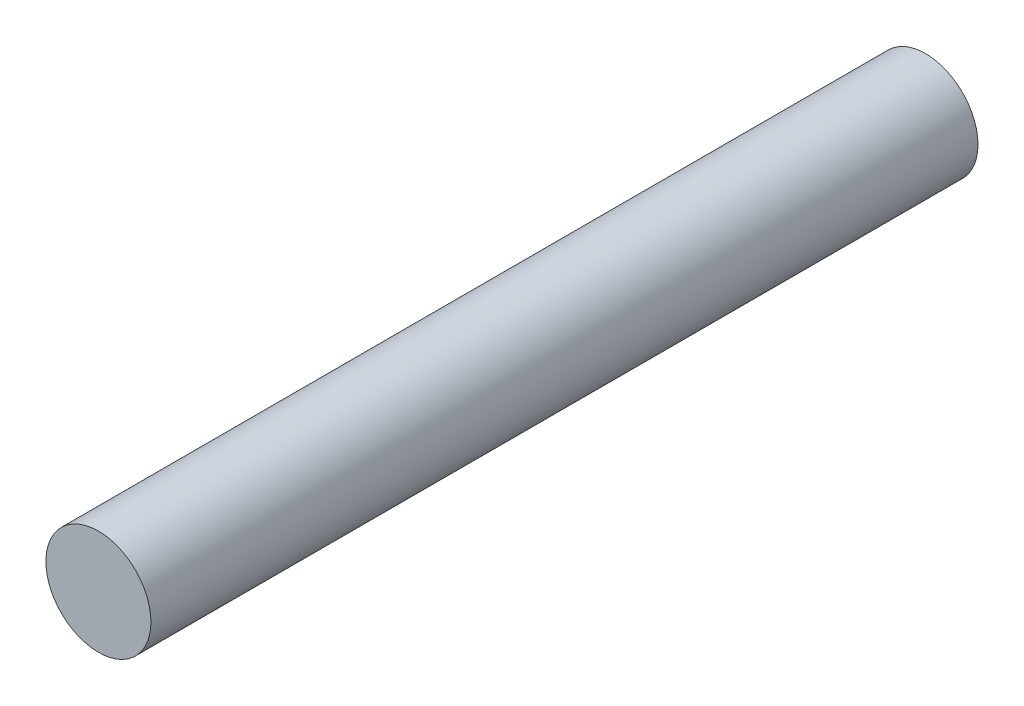
SolidWorks part; units mm, degrees
ref_plane "Alzado" through (0, 0, 0) normal (0, 0, 1) x (1, 0, 0)
ref_plane "Planta" through (0, 0, 0) normal (0, 1, 0) x (1, 0, 0)
ref_plane "Vista lateral" through (0, 0, 0) normal (1, 0, 0) x (0, 0, -1)
sketch "Croquis1" plane through (0, 0, 0) normal (0, 0, 1) x (1, 0, 0)
  circle A0 centre (0, 0) radius 3.175
  dimension "D1" = 6.35
extrude "Saliente-Extruir1" add sketch "Croquis1" along normal mid plane 50
